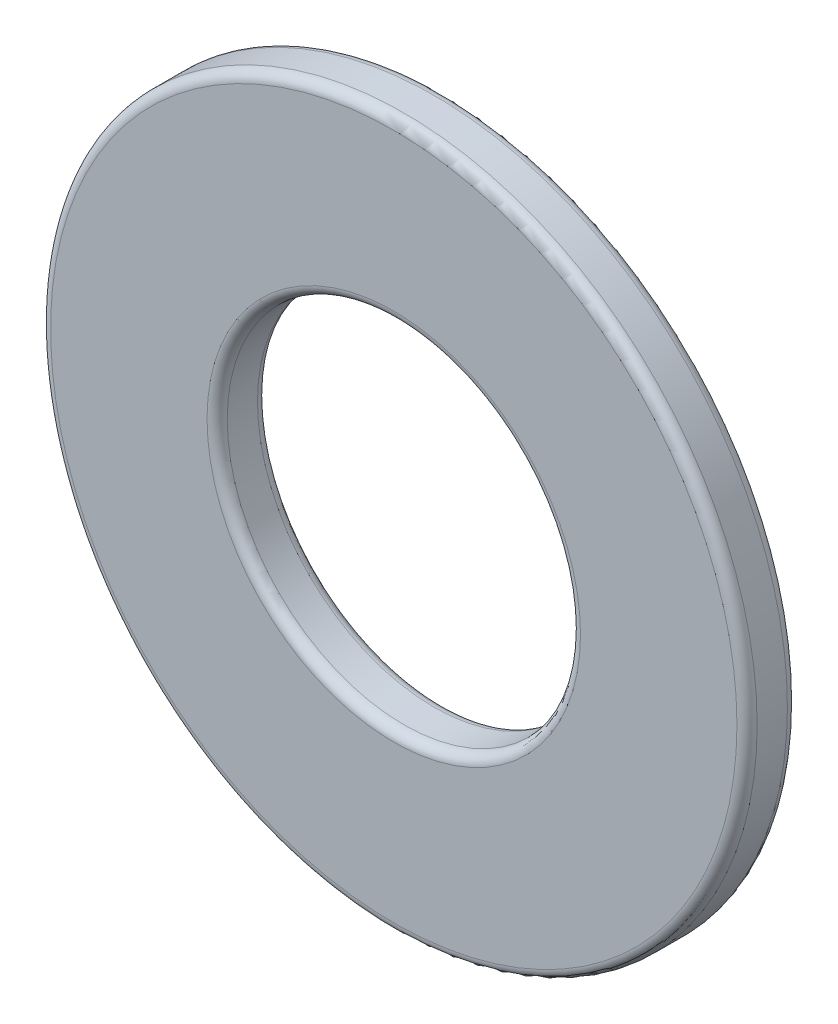
SolidWorks part; units mm, degrees
material "AISI 1035 Acier (SS)"
ref_plane "Plan de face" through (0, 0, 0) normal (0, 0, 1) x (1, 0, 0)
ref_plane "Plan de dessus" through (0, 0, 0) normal (0, 1, 0) x (1, 0, 0)
ref_plane "Plan de droite" through (0, 0, 0) normal (1, 0, 0) x (0, 0, -1)
sketch "Esquisse1" plane through (0, 0, 0) normal (0, 0, 1) x (1, 0, 0)
  circle A0 centre (0, 0) radius 3.5
  circle A1 centre (0, 0) radius 7
  dimension "D1" = 7
  dimension "D2" = 14
extrude "Boss.-Extru.1" add sketch "Esquisse1" along normal blind 1
fillet "Congé1" radius 0.2 3 edges at (3.5, 0, 1) (7, 0, 0) (7, 0, 1)
fillet "Congé2" radius 0.2 1 edges at (3.5, 0, 0)
